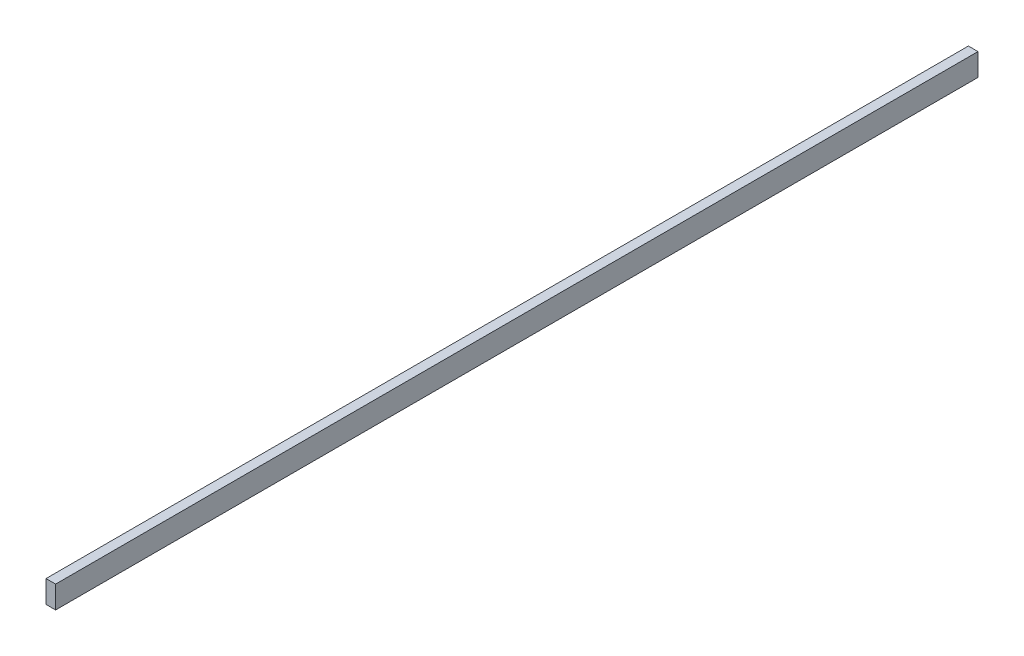
SolidWorks part; units mm, degrees
ref_plane "Front" through (0, 0, 0) normal (0, 0, 1) x (1, 0, 0)
ref_plane "Top" through (0, 0, 0) normal (0, 1, 0) x (1, 0, 0)
ref_plane "Right" through (0, 0, 0) normal (1, 0, 0) x (0, 0, -1)
sketch "Sketch1" plane through (0, 0, 0) normal (0, 0, 1) x (1, 0, 0)
  line L0 (-19.05, 44.45) -> (19.05, -44.45) construction
  line L1 (-19.05, 44.45) -> (19.05, 44.45)
  line L2 (-19.05, 44.45) -> (-19.05, -44.45)
  line L3 (-19.05, -44.45) -> (19.05, -44.45)
  line L4 (19.05, 44.45) -> (19.05, -44.45)
  dimension "D1" = 38.1
  dimension "D2" = 88.9
extrude "Extrude1" add sketch "Sketch1" along normal mid plane 3657.6
